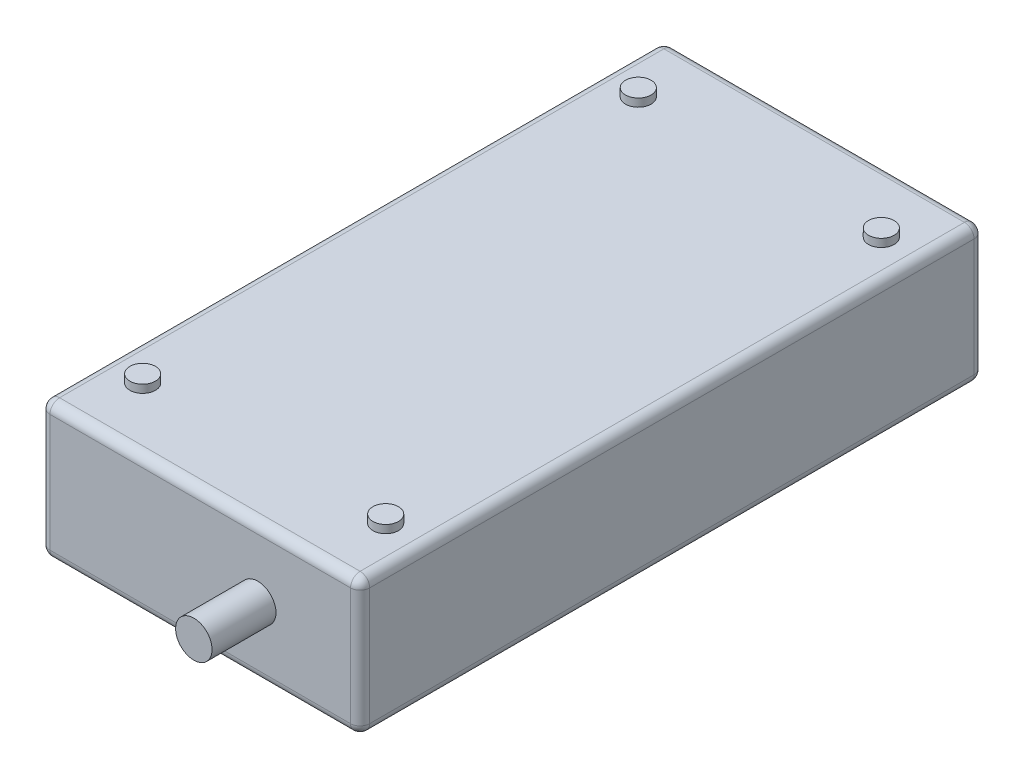
SolidWorks part; units mm, degrees
ref_plane "Front Plane" through (0, 0, 0) normal (0, 0, 1) x (1, 0, 0)
ref_plane "Top Plane" through (0, 0, 0) normal (0, 1, 0) x (1, 0, 0)
ref_plane "Right Plane" through (0, 0, 0) normal (1, 0, 0) x (0, 0, -1)
sketch "Sketch1" plane through (0, 0, 0) normal (0, 0, 1) x (1, 0, 0)
  line L1 (-29.2761, 20.3996) -> (70.7239, 20.3996)
  line L2 (-29.2761, 20.3996) -> (-29.2761, -22.3704)
  line L3 (-29.2761, -22.3704) -> (70.7239, -22.3704)
  line L4 (70.7239, 20.3996) -> (70.7239, -22.3704)
  dimension "D1" = 42.77
  dimension "D2" = 100
extrude "Boss-Extrude1" add sketch "Sketch1" along normal blind 195
sketch "Sketch2" plane through (0, 20.3996, 0) normal (0, 1, 0) x (1, 0, 0)
  line L0 (-29.2761, -97.5) -> (70.7239, -97.5) construction
  line L1 (70.7239, 0) -> (58.7239, 0)
  line L2 (70.7239, 0) -> (70.7239, -20)
  line L3 (70.7239, -20) -> (58.7239, -20)
  line L4 (58.7239, 0) -> (58.7239, -20)
  line L5 (-29.2761, -195) -> (-29.2761, 0) construction
  line L6 (70.7239, -195) -> (70.7239, 0) construction
  line L7 (20.7239, 0) -> (20.7239, -195) construction
  line L8 (70.7239, 0) -> (-29.2761, 0) construction
  line L9 (70.7239, -195) -> (-29.2761, -195) construction
  circle A0 centre (58.7239, -20) radius 4
  circle A1 centre (58.7239, -175) radius 4
  circle A2 centre (-17.2761, -20) radius 4
  circle A3 centre (-17.2761, -175) radius 4
  dimension "D3" = 8
  dimension "D1" = 12
  dimension "D2" = 20
extrude "Boss-Extrude2" add sketch "Sketch2" along normal blind 2.5 contours L3 A0 L4 | L4 A0 L3 | A2 | A3 | A1
fillet "Fillet1" radius 3 12 edges at (20.7239, -22.3704, 0) (20.7239, -22.3704, 195) (-29.2761, -0.9854, 195) (-29.2761, -22.3704, 97.5) (70.7239, -22.3704, 97.5) (70.7239, -0.9854, 195) (20.7239, 20.3996, 195) (70.7239, 20.3996, 97.5) (70.7239, -0.9854, 0) (-29.2761, -0.9854, 0) (20.7239, 20.3996, 0) (-29.2761, 20.3996, 97.5)
sketch "Sketch3" plane through (0, 0, 195) normal (0, 0, 1) x (1, 0, 0)
  line L0 (70.7239, -0.9854) -> (38.7239, -0.9854)
  line L1 (70.7239, 17.3996) -> (70.7239, -19.3704) construction
  circle A0 centre (38.7239, -0.9854) radius 5.7
  dimension "D2" = 11.4
  dimension "D1" = 32
extrude "Boss-Extrude3" add sketch "Sketch3" along normal blind 20
sketch "Sketch4" plane through (0, 0, 0) normal (0, 0, -1) x (-1, 0, 0)
  line L0 (-70.7239, 0) -> (-50.7239, 0) construction
  line L1 (-70.7239, -19.3704) -> (-70.7239, 17.3996) construction
  line L2 (-50.7239, 0) -> (-50.7239, -3)
  line L3 (-50.7239, 0) -> (-50.7239, 9)
  line L4 (-50.7239, 9) -> (-25.7239, 9)
  line L5 (-25.7239, 9) -> (-25.7239, -3)
  line L6 (-25.7239, -3) -> (-31.3502, -8.6263)
  line L7 (-50.7239, -3) -> (-45.0976, -8.6263)
  line L8 (-45.0976, -8.6263) -> (-31.3502, -8.6263)
  dimension "D1" = 20
  dimension "D2" = 3
  dimension "D3" = 9
  dimension "D4" = 25
extrude "Cut-Extrude1" cut sketch "Sketch4" against normal blind 23
sketch "Sketch5" plane through (0, 0, 23) normal (0, 0, -1) x (-1, 0, 0)
  line L0 (-37.9852, 0) -> (-37.9852, 5.4128) construction
  line L1 (-39.369, 0) -> (-36.6013, 0)
  line L2 (-39.369, 0) -> (-39.369, -5.0427)
  line L3 (-39.369, -5.0427) -> (-36.6013, -5.0427)
  line L4 (-36.6013, 0) -> (-36.6013, -5.0427)
  line L5 (-46.5649, 5.4128) -> (-43.9817, 5.4128)
  line L6 (-46.5649, 5.4128) -> (-46.5649, 1.7841)
  line L7 (-46.5649, 1.7841) -> (-43.9817, 1.7841)
  line L8 (-43.9817, 5.4128) -> (-43.9817, 1.7841)
  line L9 (-31.9886, 5.4128) -> (-31.9886, 1.7841)
  line L10 (-29.4055, 1.7841) -> (-31.9886, 1.7841)
  line L11 (-29.4055, 5.4128) -> (-29.4055, 1.7841)
  line L12 (-29.4055, 5.4128) -> (-31.9886, 5.4128)
extrude "Boss-Extrude4" add sketch "Sketch5" along normal blind 20
sketch "Sketch6" plane through (0, 0, 3) normal (0, 0, -1) x (-1, 0, 0)
  line L0 (-36.6013, -5.0427) -> (-36.6013, 0) construction
  line L1 (-39.369, 0) -> (-36.6013, 0)
  line L2 (-39.369, 0) -> (-39.369, -5.0427)
  line L3 (-39.369, -5.0427) -> (-36.6013, -5.0427)
  line L4 (-36.6013, 0) -> (-36.6013, -5.0427)
extrude "Boss-Extrude5" add sketch "Sketch6" along normal blind 3
